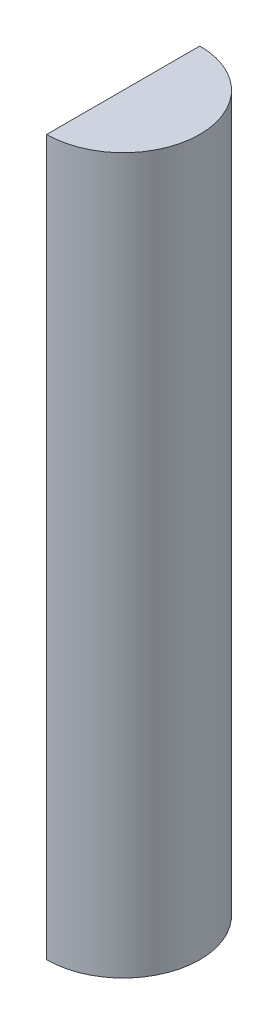
SolidWorks part; units mm, degrees
ref_plane "Front Plane" through (0, 0, 0) normal (0, 0, 1) x (1, 0, 0)
ref_plane "Top Plane" through (0, 0, 0) normal (0, 1, 0) x (1, 0, 0)
ref_plane "Right Plane" through (0, 0, 0) normal (1, 0, 0) x (0, 0, -1)
sketch "Sketch2" plane through (0, 0, 0) normal (0, 1, 0) x (1, 0, 0)
  line L0 (0, 19.05) -> (0, -19.05)
  arc A0 (0, -19.05) -> (0, 19.05) centre (0, 0) ccw
extrude "Boss-Extrude4" add sketch "Sketch2" along normal blind 177.8
